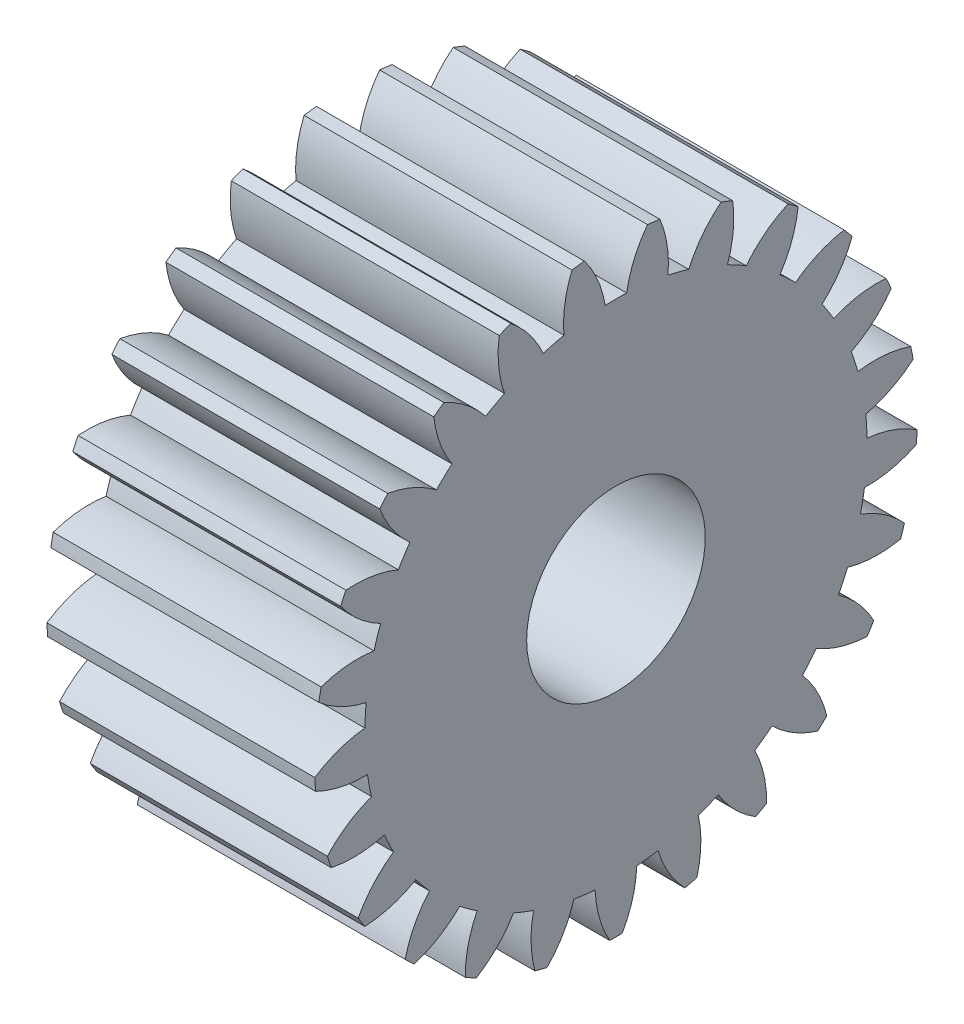
SolidWorks part; units mm, degrees
ref_plane "Plane1" through (0, 0, 0) normal (0, 0, 1) x (1, 0, 0)
ref_plane "Plane2" through (0, 0, 0) normal (0, 1, 0) x (1, 0, 0)
ref_plane "Plane3" through (0, 0, 0) normal (1, 0, 0) x (0, 0, -1)
sketch "HoldingSke" plane through (0, 0, 0) normal (0, 1, 0) x (1, 0, 0)
  line L0 (0, 0) -> (0.9063, -0.4226)
  line L1 (-15, 0) -> (100, 0) construction
  line L2 (0, 0) -> (-2.1039, 2.3779)
  line L3 (0, 0) -> (-11.863, 4.5341)
  line L4 (0, 0) -> (7.8269, 3.6497)
  line L5 (0, 0) -> (-46.8476, -17.4728)
  line L6 (0, 0) -> (-9.9476, -6.7116)
  line L7 (-2.1039, 2.3779) -> (8.6586, 51.2059)
  line L8 (-76.2, 54.61) -> (-74.8, 54.61)
  line L9 (-71.009, 38.7566) -> (-53.1078, 45.2721)
  line L10 (-76.2, 71.12) -> (104.1128, 71.12)
  line L11 (0, 0) -> (-12, 0)
  line L12 (-76.2, 101.6) -> (-76.162, 101.6)
  line L13 (24.9733, 27.94) -> (52.9518, 28.4284)
  line L14 (24.9733, 27.94) -> (24.9743, 27.94)
  line L15 (24.9733, 27.94) -> (100.4006, 29.5858)
  line L16 (-63.627, -1) -> (-12.827, -1)
  circle A0 centre (0, 0) radius 4
  circle A1 centre (0, 0) radius 11.249
  circle A2 centre (0, 0) radius 37.5
  circle A3 centre (0, 0) radius 4
  dimension "MHD" = 22.498
  dimension "Hub_dia" = 75
  dimension "Bore" = 8
  dimension "MBD" = 8
  dimension "Num_teeth" = 25
  dimension "Pitch" = 1
  dimension "Overall_len" = 50
  dimension "Show_teeth" = 25
  dimension "Thickness" = 12
  dimension "OAL" = 50.0001
  dimension "T_dim" = 1.4
  dimension "Ap" = 20
  dimension "H" = 19.05
  dimension "Pitch_radius" = 180.3128
  dimension "Width" = 12
  dimension "Backlash" = 0.038
  dimension "Addendum_fac" = 1
  dimension "Dedendum_fac" = 1.25
  dimension "Clearance_fac" = 0.25
  dimension "Dedendum_add" = 0.001
  dimension "Module" = 1
sketch "BasProSke" plane through (0, 0, 0) normal (0, 1, 0) x (1, 0, 0)
  line L0 (-10, 0) -> (60, 0) construction
  line L1 (0, 0) -> (0, 13.5)
  line L2 (0, 0) -> (12, 0)
  line L3 (12, 0) -> (12, 13.5)
  line L4 (12, 13.5) -> (0, 13.5)
  dimension "Thickness" = 12
  dimension "Diameter" = 27
revolve "Base-Revolve" add sketch "BasProSke" angle 360 about L0
sketch "TooCutSke" plane through (0, 0, 0) normal (1, 0, 0) x (0, 0, -1)
  line L1 (0, 0) -> (0, 107) construction
  line L2 (0, 0) -> (-0.8514, 12.471) construction
  line L3 (0, 0) -> (-3.1282, 24.7619) construction
  line L4 (-0.8514, 12.471) -> (-1.5641, 12.3809) construction
  arc A0 (0.4801, 11.2388) -> (-0.4801, 11.2388) centre (0, 0) ccw
  arc A1 (1.4322, 13.4494) -> (-1.4322, 13.4494) centre (0, 0) ccw
  circle A2 centre (0, 0) radius 12.5 construction
  circle A3 centre (0, 0) radius 11.7462 construction
  arc A4 (-0.4801, 11.2388) -> (-1.4322, 13.4494) centre (-5.4133, 10.4244) ccw
  arc A5 (1.4322, 13.4494) -> (0.4801, 11.2388) centre (5.4133, 10.4244) ccw
  dimension "Root_dia" = 22.498
  dimension "Overcut_dia" = 27.0508
  dimension "Pitch_dia" = 25
  dimension "Base_dia" = 23.4923
  dimension "Flank_rad" = 5
  dimension "Half_ang" = 7.2
  dimension "Half_CT" = 0.7184
extrude "ToothCut" cut sketch "TooCutSke" along normal through all
fillet "Breaks" [suppressed] radius 0.02
fillet "RootFillets" [suppressed] radius 0.251
pattern_circular "TeethCuts" count 25 every 14.4 about axis through (-10, 0, 0) along (1, 0, 0) of "ToothCut", "RootFillets", "Breaks"
sketch "HubNeaOneSke" plane through (0, 0, 0) normal (-1, 0, 0) x (0, 0, 1)
  circle A0 centre (0, 0) radius 11.249
  dimension "Diameter" = 22.498
extrude "HubNearOne" [suppressed] add sketch "HubNeaOneSke" along normal blind 38.0001
sketch "HubNeaBotSke" plane through (0, 0, 0) normal (-1, 0, 0) x (0, 0, 1)
  circle A0 centre (0, 0) radius 11.249
  dimension "Diameter" = 22.498
extrude "HubNearBoth" [suppressed] add sketch "HubNeaBotSke" along normal blind 19
ref_plane "FarPln" through (12, 0, 0) normal (1, 0, 0) x (0, 0, -1)
sketch "HubFarSke" plane through (12, 0, 0) normal (1, 0, 0) x (0, 0, -1)
  circle A0 centre (0, 0) radius 11.249
  dimension "Diameter" = 22.498
extrude "HubFar" [suppressed] add sketch "HubFarSke" along normal blind 19
sketch "BorSke" plane through (0, 0, 0) normal (1, 0, 0) x (0, 0, -1)
  circle A0 centre (0, 0) radius 4
  dimension "Diameter" = 8
extrude "Bore" cut sketch "BorSke" along normal mid plane 100.0001
sketch "KeySke" plane through (0, 0, 0) normal (1, 0, 0) x (0, 0, -1)
  line L0 (-1, 0) -> (-1, 5.4)
  line L1 (-1, 5.4) -> (1, 5.4)
  line L2 (1, 5.4) -> (1, 0)
  line L3 (0, 0) -> (0, 34) construction
  line L4 (-1, 0) -> (1, 0)
  dimension "Offset" = 5.4
  dimension "Width" = 2
extrude "Keyway" [suppressed] cut sketch "KeySke" along normal mid plane 100.0001
pattern_circular "Keyway2" [suppressed] count 2 every 90 about axis through (-10, 0, 0) along (1, 0, 0)
equation "' \"Module@HoldingSke\" = 6.35"
equation "' \"Num_teeth@HoldingSke\" = 12"
equation "' \"Ap@HoldingSke\" =  20"
equation "' \"Ap@HoldingSke\" = 20"
equation "' \"Width@HoldingSke\" = 0.5 * 25.4"
equation "' \"Hub_dia@HoldingSke\"= 1 * 25.4"
equation "' \"Hub_dia@HoldingSke\" = 1 * 25.4"
equation "' \"Overall_len@HoldingSke\" = 1.0 * 25.4"
equation "' \"Bore@HoldingSke\" = 0.75 * 25.4"
equation "' \"T_dim@HoldingSke\" = 0.1 * 25.4"
equation "' \"Width@KeySke\" = 0.25 * 25.4"
equation "' \"Show_teeth@HoldingSke\" = 13"
equation "' \"Backlash@HoldingSke\" = 0.009 * 25.4"
equation "' \"Addendum_fac@HoldingSke\" = 1.0"
equation "' \"Dedendum_fac@HoldingSke\" = 1.25"
equation "' \"Dedendum_add@HoldingSke\" = 0.00005 * 25.4"
equation "' \"Clearance_fac@HoldingSke\" = 0.25"
equation "\"Pitch@HoldingSke\" = 1 / \"Module@HoldingSke\""
equation "\"Overcut_dia@TooCutSke\" = (\"Num_teeth@HoldingSke\" + 2 * \"Addendum_fac@HoldingSke\") / \"Pitch@HoldingSke\" + 0.002 * 25.4"
equation "\"Pitch_dia@TooCutSke\" = \"Num_teeth@HoldingSke\" / \"Pitch@HoldingSke\""
equation "\"Base_dia@TooCutSke\" = \"Num_teeth@HoldingSke\" / \"Pitch@HoldingSke\" * cos((\"Ap@HoldingSke\"  * 3.14159265 / 180))"
equation "\"Root_dia@TooCutSke\" = (\"Num_teeth@HoldingSke\" + 2) / \"Pitch@HoldingSke\" - 2 * (\"Addendum_fac@HoldingSke\" + \"Dedendum_fac@HoldingSke\") / \"Pitch@HoldingSke\" - \"Dedendum_add@HoldingSke\" * 2"
equation "\"Half_ang@TooCutSke\" = 180 / \"Num_teeth@HoldingSke\""
equation "\"Half_CT@TooCutSke\" = \"Num_teeth@HoldingSke\" / \"Pitch@HoldingSke\" * sin((3.14159265 / 2 / \"Num_teeth@HoldingSke\")) / 2 - 7 * \"Backlash@HoldingSke\" / 4"
equation "\"Flank_rad@TooCutSke\" = \"Num_teeth@HoldingSke\" / \"Pitch@HoldingSke\" / 5"
equation "\"Radius@RootFillets\" = \"Clearance_fac@HoldingSke\" / \"Pitch@HoldingSke\" + \"Dedendum_add@HoldingSke\""
equation "\"Break_rad@Breaks\" = 0.02 / \"Pitch@HoldingSke\""
equation "\"Thickness@HoldingSke\" = \"Width@HoldingSke\""
equation "\"OAL@HoldingSke\" = \"Thickness@HoldingSke\""
equation "\"MHD@HoldingSke\" = (\"Num_teeth@HoldingSke\" + 2) / \"Pitch@HoldingSke\" - 2 * (\"Addendum_fac@HoldingSke\" + \"Dedendum_fac@HoldingSke\")  / \"Pitch@HoldingSke\" - \"Dedendum_add@HoldingSke\" * 2"
equation "\"MBD@HoldingSke\" = (\"Num_teeth@HoldingSke\" + 2) / \"Pitch@HoldingSke\" - 2 * (\"Addendum_fac@HoldingSke\" + \"Dedendum_fac@HoldingSke\")  / \"Pitch@HoldingSke\" - \"Dedendum_add@HoldingSke\" * 2 - 0.002 * 25.4"
equation "\"MHD@HoldingSke\" = ((sgn( \"MHD@HoldingSke\" - \"Hub_dia@HoldingSke\" )-1)*( \"MHD@HoldingSke\" - \"Hub_dia@HoldingSke\" ))/-2+ \"Hub_dia@HoldingSke\""
equation "\"MBD@HoldingSke\" = ((sgn( \"MBD@HoldingSke\" - \"Bore@HoldingSke\" )-1)*( \"MBD@HoldingSke\" - \"Bore@HoldingSke\" ))/-2+ \"Bore@HoldingSke\""
equation "\"OAL@HoldingSke\" = ((sgn( \"OAL@HoldingSke\" - \"Overall_len@HoldingSke\" )+1)*( \"OAL@HoldingSke\" - \"Overall_len@HoldingSke\" ))/2 + \"Overall_len@HoldingSke\" + 0.000002 * 25.4"
equation "\"Num_teeth@TeethCuts\" = int( \"Show_teeth@HoldingSke\" ) + 1"
equation "\"Num_teeth@TeethCuts\" = ((sgn( \"Num_teeth@TeethCuts\" - \"Num_teeth@HoldingSke\" )-1)*( \"Num_teeth@TeethCuts\" - \"Num_teeth@HoldingSke\" ))/-2+ \"Num_teeth@HoldingSke\""
equation "\"Num_teeth@TeethCuts\" = ((sgn( \"Num_teeth@TeethCuts\" - 2.0)+1)*( \"Num_teeth@TeethCuts\" - 2.0))/2 +2.0"
equation "\"Angle@TeethCuts\" = 360.0 / \"Num_teeth@HoldingSke\""
equation "\"Diameter@BasProSke\" = (\"Num_teeth@HoldingSke\" + 2 * \"Addendum_fac@HoldingSke\") / \"Pitch@HoldingSke\""
equation "\"Thickness@BasProSke\"  = \"Thickness@HoldingSke\""
equation "' \"Fillet_rad@BasProSke\" =  \"Thickness@HoldingSke\" * 0.05"
equation "' \"Fillet_rad@BasProSke\" = \"Thickness@HoldingSke\" * 0.05"
equation "\"MHD@HoldingSke\" = ((sgn( \"MHD@HoldingSke\" - \"Root_dia@TooCutSke\" )-1)*( \"MHD@HoldingSke\" - \"Root_dia@TooCutSke\" ))/-2+ \"Root_dia@TooCutSke\""
equation "\"Diameter@HubNeaOneSke\" = \"MHD@HoldingSke\""
equation "\"Length@HubNearOne\" = \"OAL@HoldingSke\" - \"Thickness@BasProSke\""
equation "\"Diameter@HubNeaBotSke\" = \"MHD@HoldingSke\""
equation "\"Length@HubNearBoth\" = ( \"OAL@HoldingSke\" - \"Thickness@BasProSke\" ) / 2.0"
equation "\"Thickness@FarPln\" = \"Thickness@BasProSke\""
equation "\"Diameter@HubFarSke\" = \"MHD@HoldingSke\""
equation "\"Length@HubFar\" = ( \"OAL@HoldingSke\" - \"Thickness@BasProSke\" ) / 2.0"
equation "\"Diameter@BorSke\" = \"MBD@HoldingSke\""
equation "\"D1@Bore\" = \"OAL@HoldingSke\" * 2.0"
equation "\"D1@Keyway\" = \"OAL@HoldingSke\" * 2.0"
equation "\"Offset@KeySke\" = \"T_dim@HoldingSke\" + \"MBD@HoldingSke\" / 2.0"
